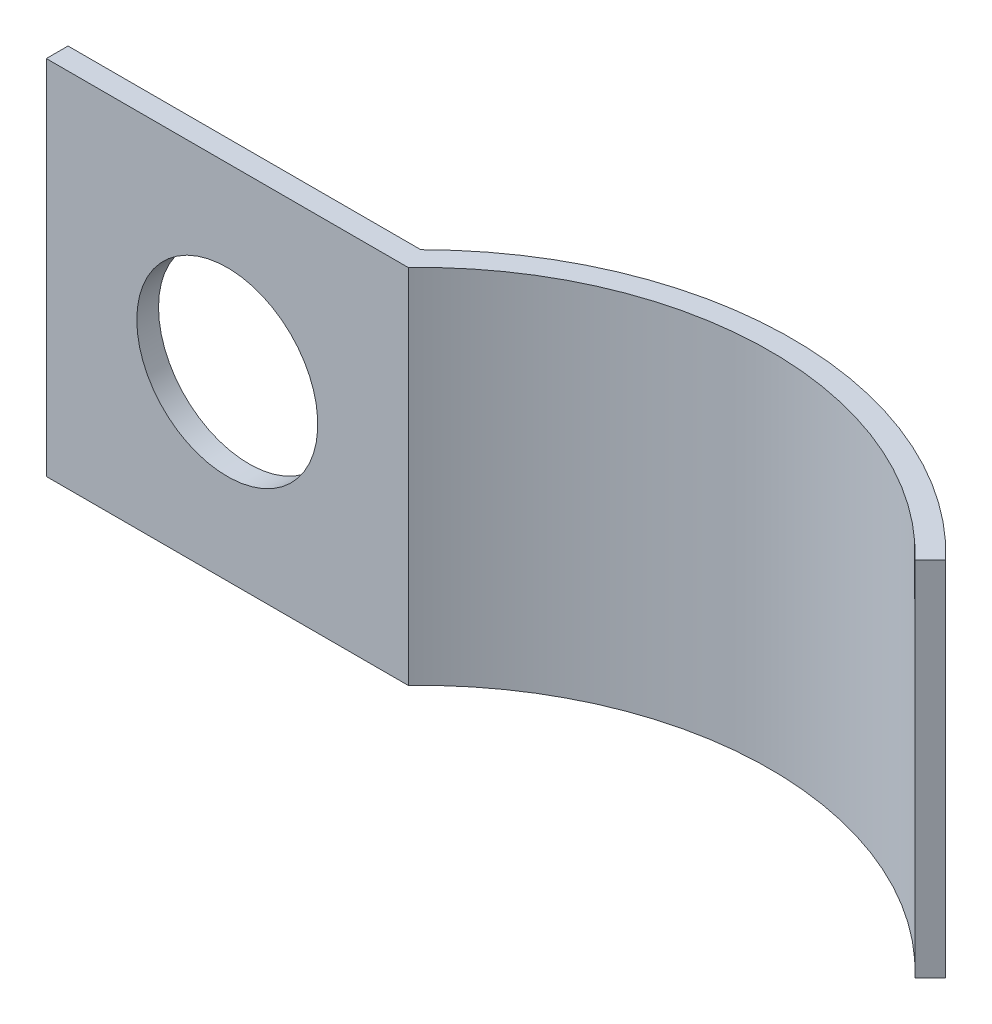
SolidWorks part; units mm, degrees
ref_plane "前视基准面" through (0, 0, 0) normal (0, 0, 1) x (1, 0, 0)
ref_plane "上视基准面" through (0, 0, 0) normal (0, 1, 0) x (1, 0, 0)
ref_plane "右视基准面" through (0, 0, 0) normal (1, 0, 0) x (0, 0, -1)
other "Configuration Table"
sketch "草图1" plane through (0, 0, 0) normal (0, 1, 0) x (1, 0, 0)
  line L0 (0, 0) -> (5, 0)
  line L6 (-991, 1.5) -> (49009, 1.5) construction
  line L7 (0, 0.3) -> (4.8737, 0.3)
  line L9 (0, 0) -> (0, 0.3)
  line L11 (12, 0) -> (13.0577, -1.0088) construction
  line L12 (12.2122, 0.2122) -> (13.2647, -0.7917) construction
  line L13 (12.2122, 0.2122) -> (12, 0)
  line L14 (-995, 0) -> (49005, 0) construction
  arc A0 (5, 0) -> (12, 0) centre (8.5, -3.3333) cw
  arc A1 (4.8737, 0.3) -> (12.2122, 0.2122) centre (8.5, -3.3333) cw
  point P10 (8.5, 1.5)
  point P14 (0, 0)
  point P15 (12.2139, 0.2104)
  dimension "D4" = 1.5
  dimension "D1" = 7
  dimension "D2" = 5
  dimension "D3" = 45
  dimension "D5" = 0.3
extrude "凸台-拉伸1" add sketch "草图1" along normal blind 5
sketch "草图2" plane through (0, 0, -0.3) normal (0, 0, -1) x (-1, 0, 0)
  line L0 (-1000, 2.5) -> (49000, 2.5) construction
  line L1 (0, 5) -> (0, 0) construction
  circle A0 centre (-2.5, 2.5) radius 1.25
  point P3 (0, 0)
  point P7 (0, 2.5)
  dimension "D1" = 2.5
  dimension "D2" = 2.5
extrude "切除-拉伸1" cut sketch "草图2" against normal blind 5
